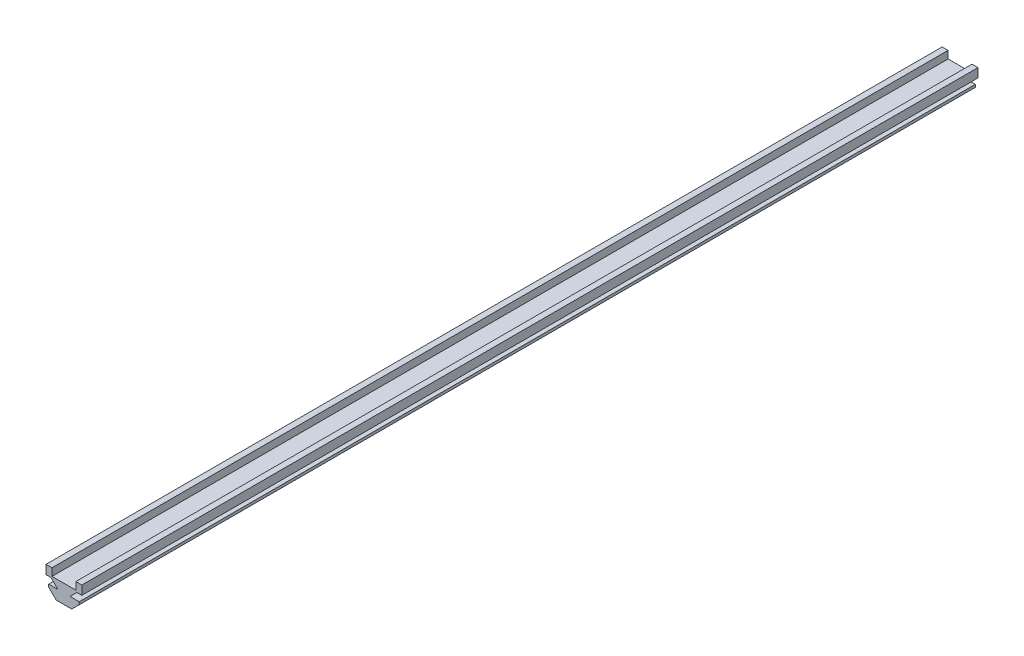
SolidWorks part; units mm, degrees
ref_plane "Alzado" through (0, 0, 0) normal (0, 0, 1) x (1, 0, 0)
ref_plane "Planta" through (0, 0, 0) normal (0, 1, 0) x (1, 0, 0)
ref_plane "Vista lateral" through (0, 0, 0) normal (1, 0, 0) x (0, 0, -1)
sketch "Croquis1" plane through (0, 0, 0) normal (0, 0, 1) x (1, 0, 0)
  line L0 (12.6279, -5.675) -> (15.1, -3.2029)
  line L8 (7.1649, -6.175) -> (10, -6.175)
  line L9 (15.1, -2.3) -> (15.1, -3.2029)
  line L10 (15.1, -2.3) -> (12.0429, -2.3)
  line L12 (7.3721, -5.675) -> (12.6279, -5.675)
  line L13 (10, -6.175) -> (10, 0.5) construction
  line L33 (7.3721, -5.675) -> (4.9, -3.2029)
  line L34 (4.9, -2.3) -> (4.9, -3.2029)
  line L35 (4.9, -2.3) -> (7.9571, -2.3)
  line L41 (12.0429, -2.3) -> (14.3429, 0)
  line L42 (7.9571, -2.3) -> (5.6571, 0)
  line L43 (14.3429, 0) -> (16, 0)
  line L49 (16, 0) -> (16, 3)
  line L50 (14, 3) -> (16, 3)
  line L51 (10, 0.5) -> (10, -6.175)
  line L54 (6, 0.5) -> (14, 0.5)
  line L56 (14, 0.5) -> (14, 3)
  line L62 (5.6571, 0) -> (4, 0)
  line L65 (7.1649, -6.175) -> (4.4, -3.4101)
  line L66 (4.4, -1.8) -> (4.4, -3.4101)
  line L67 (4.4, -1.8) -> (6.75, -1.8)
  line L68 (6.75, -1.8) -> (4.95, 0)
  line L69 (0, 0) -> (4.4, 0)
  line L70 (4.4, 0) -> (4.95, 0)
  line L75 (6, 0.5) -> (6, 3)
  line L76 (6, 3) -> (4, 3)
  line L77 (4, 0) -> (4, 3)
  line L89 (10, 0.5) -> (6, 0.5)
  point P3 (10, -5.675)
  dimension "D1" = 10
  dimension "D2" = 4
  dimension "D5" = 2
  dimension "D4" = 3
  dimension "D6" = 0.5
extrude "Saliente-Extruir1" add sketch "Croquis1" along normal blind 300 contours L77 L62 L42 L35 L34 L33 L12 L51 L54 L75 L76 | L56 L54 L51 L12 L0 L9 L10 L41 L43 L49 L50
